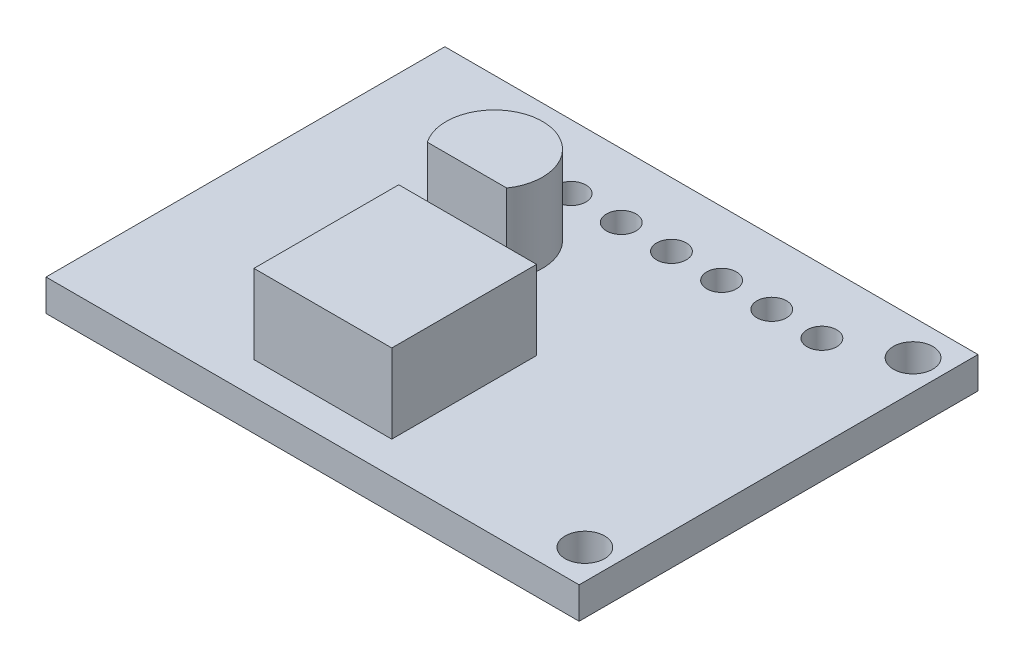
SolidWorks part; units mm, degrees
ref_plane "Front Plane" through (0, 0, 0) normal (0, 0, 1) x (1, 0, 0)
ref_plane "Top Plane" through (0, 0, 0) normal (0, 1, 0) x (1, 0, 0)
ref_plane "Right Plane" through (0, 0, 0) normal (1, 0, 0) x (0, 0, -1)
sketch "Sketch1" plane through (0, 0, 0) normal (0, 1, 0) x (1, 0, 0)
  line L1 (-13.5, -10.1) -> (13.5, -10.1)
  line L2 (-13.5, -10.1) -> (-13.5, 10.1)
  line L3 (-13.5, 10.1) -> (13.5, 10.1)
  line L4 (13.5, -10.1) -> (13.5, 10.1)
  line L5 (-13.5, -10.1) -> (13.5, 10.1) construction
  line L6 (-13.5, 10.1) -> (13.5, -10.1) construction
  point P0 (0, 0)
  dimension "D1" = 20.2
  dimension "D2" = 27
extrude "Boss-Extrude1" add sketch "Sketch1" along normal blind 1.6
sketch "Sketch2" plane through (0, 1.6, 0) normal (0, 1, 0) x (1, 0, 0)
  line L0 (12, -8.3105) -> (12, 8.3105) construction
  circle A0 centre (12, 8.3105) radius 1
  circle A1 centre (12, -8.3105) radius 1
  point P4 (12, 0)
  dimension "D1" = 2
  dimension "D2" = 16.6211
  dimension "D3" = 12
extrude "Cut-Extrude1" cut sketch "Sketch2" against normal through all
sketch "Sketch4" plane through (0, 1.6, 0) normal (0, 1, 0) x (1, 0, 0)
  line L0 (8.835, 6.8597) -> (-9.3221, 6.8597) construction
  circle A0 centre (8.835, 6.8597) radius 0.75
  circle A1 centre (6.295, 6.8597) radius 0.75
  circle A2 centre (3.755, 6.8597) radius 0.75
  circle A3 centre (1.215, 6.8597) radius 0.75
  circle A4 centre (-1.325, 6.8597) radius 0.75
  circle A5 centre (-3.865, 6.8597) radius 0.75
  dimension "D1" = 1.5
  dimension "D2" = 6
extrude "Cut-Extrude2" cut sketch "Sketch4" against normal through all
sketch "Sketch6" plane through (0, 1.6, 0) normal (0, 1, 0) x (1, 0, 0)
  line L1 (-4.6137, -1.123) -> (2.3677, -1.123)
  line L2 (-4.6137, -1.123) -> (-4.6137, -8.4562)
  line L3 (-4.6137, -8.4562) -> (2.3677, -8.4562)
  line L4 (2.3677, -1.123) -> (2.3677, -8.4562)
extrude "Boss-Extrude2" add sketch "Sketch6" along normal blind 4
sketch "Sketch7" plane through (0, 1.6, 0) normal (0, 1, 0) x (1, 0, 0)
  line L1 (-5.7586, 1.469) -> (-1.7369, 1.469)
  arc A0 (-1.7369, 1.469) -> (-5.7586, 1.469) centre (-3.7478, 2.8548) ccw
extrude "Boss-Extrude3" add sketch "Sketch7" along normal blind 4
